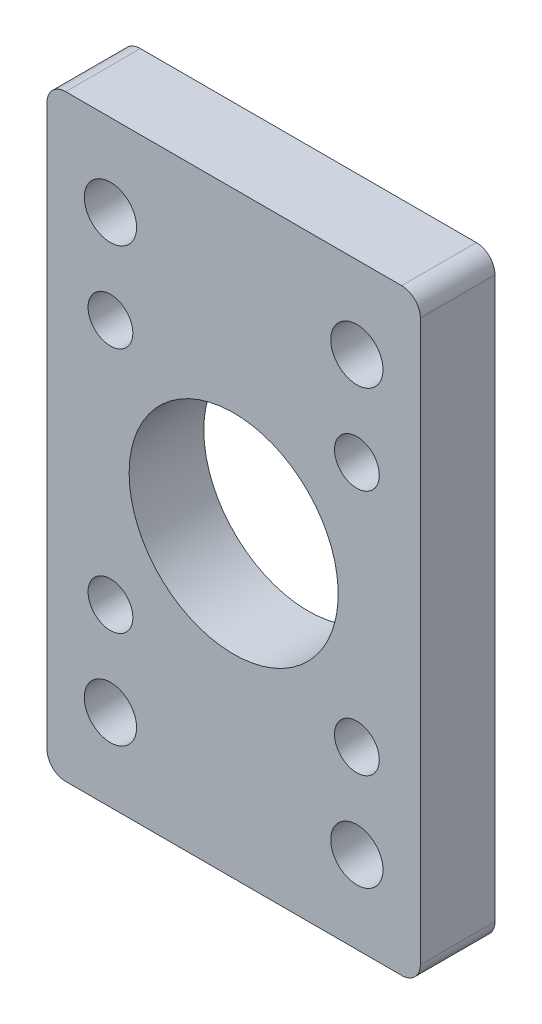
SolidWorks part; units mm, degrees
ref_plane "前视基准面" through (0, 0, 0) normal (0, 0, 1) x (1, 0, 0)
ref_plane "上视基准面" through (0, 0, 0) normal (0, 1, 0) x (1, 0, 0)
ref_plane "右视基准面" through (0, 0, 0) normal (1, 0, 0) x (0, 0, -1)
sketch "草图1" plane through (0, 0, 0) normal (0, 0, 1) x (1, 0, 0)
  line L0 (0, 0) -> (-25, 0) construction
  line L1 (-25, -40) -> (25, -40)
  line L2 (-25, -40) -> (-25, 40)
  line L3 (-25, 40) -> (25, 40)
  line L4 (25, -40) -> (25, 40)
  line L5 (-25, -40) -> (25, 40) construction
  line L6 (-25, 40) -> (25, -40) construction
  line L7 (0, 0) -> (0, 40) construction
  line L8 (0, 0) -> (0, -10) construction
  circle A0 centre (0, 0) radius 14
  circle A1 centre (-16.5, 16.5) radius 3
  circle A2 centre (-16.5, 29) radius 3.5
  point P0 (0, 0)
  dimension "BA" = 28
  dimension "D2" = 33
  dimension "缸体L" = 6
  dimension "BP" = 7
  dimension "BE" = 80
  dimension "BC" = 50
  dimension "T" = 33
  dimension "BF" = 58
  dimension "BD" = 33
  dimension "BB" = 10
sketch "草图2" plane through (0, 0, 0) normal (0, 0, 1) x (1, 0, 0)
  line L0 (-25, 40) -> (25, 40) construction
  line L1 (-25, -40) -> (-25, 40) construction
  line L2 (-25, -40) -> (25, -40) construction
  line L3 (25, -40) -> (25, 40) construction
  line L4 (-25, 40) -> (25, 40)
  line L5 (-25, -40) -> (-25, 40)
  line L6 (-25, -40) -> (25, -40)
  line L7 (25, -40) -> (25, 40)
extrude "凸台-拉伸1" add sketch "草图2" along normal blind 10
sketch "草图3" plane through (0, 0, 0) normal (0, 0, -1) x (-1, 0, 0)
  circle A0 centre (16.5, 29) radius 3.5 construction
  circle A1 centre (16.5, 16.5) radius 3 construction
  circle A2 centre (16.5, 29) radius 3.5
  circle A3 centre (16.5, 16.5) radius 3
extrude "切除-拉伸1" cut sketch "草图3" against normal through all
mirror "镜向1" about plane through (0, 0, 0) normal (1, 0, 0) of "切除-拉伸1"
mirror "镜向2" about plane through (0, 0, 0) normal (0, 1, 0) of "镜向1", "切除-拉伸1"
sketch "草图4" plane through (0, 0, 0) normal (0, 0, -1) x (-1, 0, 0)
  circle A0 centre (0, 0) radius 14 construction
  circle A1 centre (0, 0) radius 14
extrude "切除-拉伸2" cut sketch "草图4" against normal through all
fillet "圆角1" radius 2.5 4 edges at (25, -40, 5) (-25, -40, 5) (-25, 40, 5) (25, 40, 5)
equation "\"D2@草图1\" = \"T@草图1\""
equation "\"D1@凸台-拉伸1\" = \"BB@草图1\""
equation "\"D1@圆角1\" = \"BC@草图1\"*0.05"
